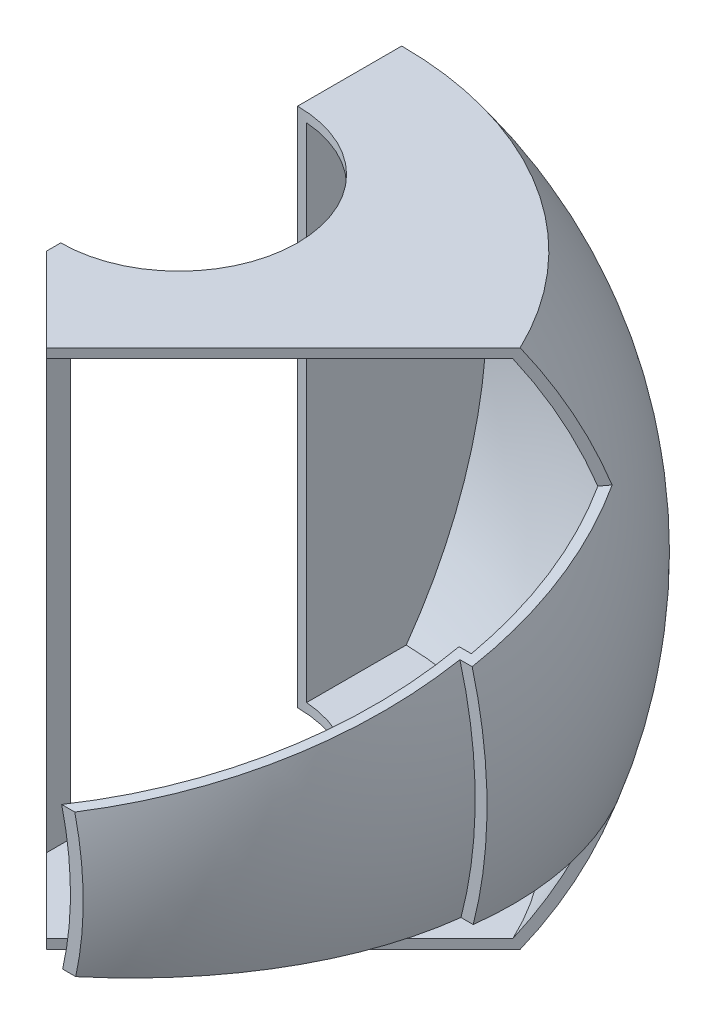
SolidWorks part; units mm, degrees
ref_plane "Front Plane" through (0, 0, 0) normal (0, 0, 1) x (1, 0, 0)
ref_plane "Top Plane" through (0, 0, 0) normal (0, 1, 0) x (1, 0, 0)
ref_plane "Right Plane" through (0, 0, 0) normal (1, 0, 0) x (0, 0, -1)
sketch "Sketch1" plane through (0, 0, 0) normal (1, 0, 0) x (0, 0, -1)
  line L0 (0, 0) -> (-113.0621, 0) construction
  line L1 (0, -55) -> (0, 55)
  line L2 (0, 55) -> (-75, 55)
  line L3 (0, -55) -> (-75, -55)
  arc A0 (-75, 55) -> (-75, -55) centre (0, 0) ccw
  dimension "D1" = 55
  dimension "D2" = 75
revolve "Revolve1" add sketch "Sketch1" angle 180 about L1
sketch "Sketch2" plane through (0, -55, 0) normal (0, -1, 0) x (1, 0, 0)
  line L0 (0, 0) -> (0, 40)
  line L1 (0, -75) -> (0, 75) construction
  line L2 (0, 40) -> (12.2873, 48.6036)
  line L4 (0, 0) -> (17.6777, 17.6777)
  line L5 (17.6777, 17.6777) -> (111.3154, -75.9601)
  line L10 (0, 0) -> (-156.1799, 0)
  line L11 (-156.1799, 0) -> (-156.1799, 130.367)
  line L12 (-156.1799, 130.367) -> (136.8657, 130.367)
  line L13 (136.8657, 130.367) -> (111.3154, -75.9601)
  dimension "D1" = 40
  dimension "D2" = 15
  dimension "D3" = 125
  dimension "D4" = 25
  dimension "D5" = 45
extrude "Cut-Extrude2" cut sketch "Sketch2" against normal through all contours L10 L11 L12 L13 L5 L4
ref_plane "Plane1" through (100, 0, 0) normal (1, 0, 0) x (0, 0, -1)
sketch "Sketch3" plane through (100, 0, 0) normal (1, 0, 0) x (0, 0, -1)
  line L0 (0, 0.4248) -> (-60, 0.4248) construction
  line L1 (-60, -14.5752) -> (-60, 15.4248)
  line L2 (0, 0.4248) -> (45.6666, 0.4248) construction
  line L3 (45.6666, -29.5752) -> (45.6666, 30.4248)
  line L4 (-60, 15.4248) -> (45.6666, 30.4248)
  line L5 (-60, -14.5752) -> (45.6666, -29.5752)
  dimension "D1" = 60
  dimension "D2" = 15
  dimension "D3" = 30
  dimension "D4" = 60
extrude "Boss-Extrude1" add sketch "Sketch3" against normal up to surface (100 mm away)
sketch "Sketch4" plane through (0, 0, 0) normal (1, 0, 0) x (0, 0, -1)
  line L0 (-74.9933, 55) -> (-155.5635, 55)
  line L1 (0, 0) -> (0, 140.7338) construction
  line L2 (-74.9933, -55) -> (-155.5635, -55)
  arc A0 (-74.9933, 55) -> (-74.9933, -55) centre (0, 0) ccw
  arc A1 (-155.5635, 55) -> (-155.5635, -55) centre (0, 0) ccw
  dimension "D1" = 330
  dimension "D2" = 186
revolve "Cut-Revolve1" cut sketch "Sketch4" angle 360 about L1
sketch "Sketch5" plane through (0, -55, 0) normal (0, -1, 0) x (1, 0, 0)
  line L0 (0, 0) -> (85.8037, 85.8037)
  line L1 (85.8037, 85.8037) -> (-52.7134, 88.0681)
  line L2 (-52.7134, 88.0681) -> (-54.1531, 0)
  line L3 (-54.1531, 0) -> (0, 0)
extrude "Cut-Extrude3" cut sketch "Sketch5" against normal through all
sketch "Sketch6" plane through (0, 0, 0) normal (1, 0, 0) x (0, 0, -1)
  line L0 (-71.8697, 55) -> (-106.6536, 55)
  line L1 (-71.8697, -55) -> (-106.6536, -55)
  line L2 (0, 0) -> (0, 106.9648) construction
  arc A0 (-71.8697, 55) -> (-71.8697, -55) centre (0, 0) ccw
  arc A1 (-106.6536, 55) -> (-106.6536, -55) centre (0, 0) ccw
  dimension "D1" = 240
  dimension "D2" = 181
revolve "Cut-Revolve2" cut sketch "Sketch6" angle 90 about L2
sketch "Sketch8" plane through (0, -55, 0) normal (0, -1, 0) x (1, 0, 0)
  line L0 (0, 0) -> (0, -28)
  line L1 (0, -74.9933) -> (0, 0) construction
  circle A0 centre (0, -28) radius 25
  dimension "D2" = 50
  dimension "D1" = 28
extrude "Cut-Extrude4" cut sketch "Sketch8" against normal through all contours A0
shell "Shell1" thickness 2
